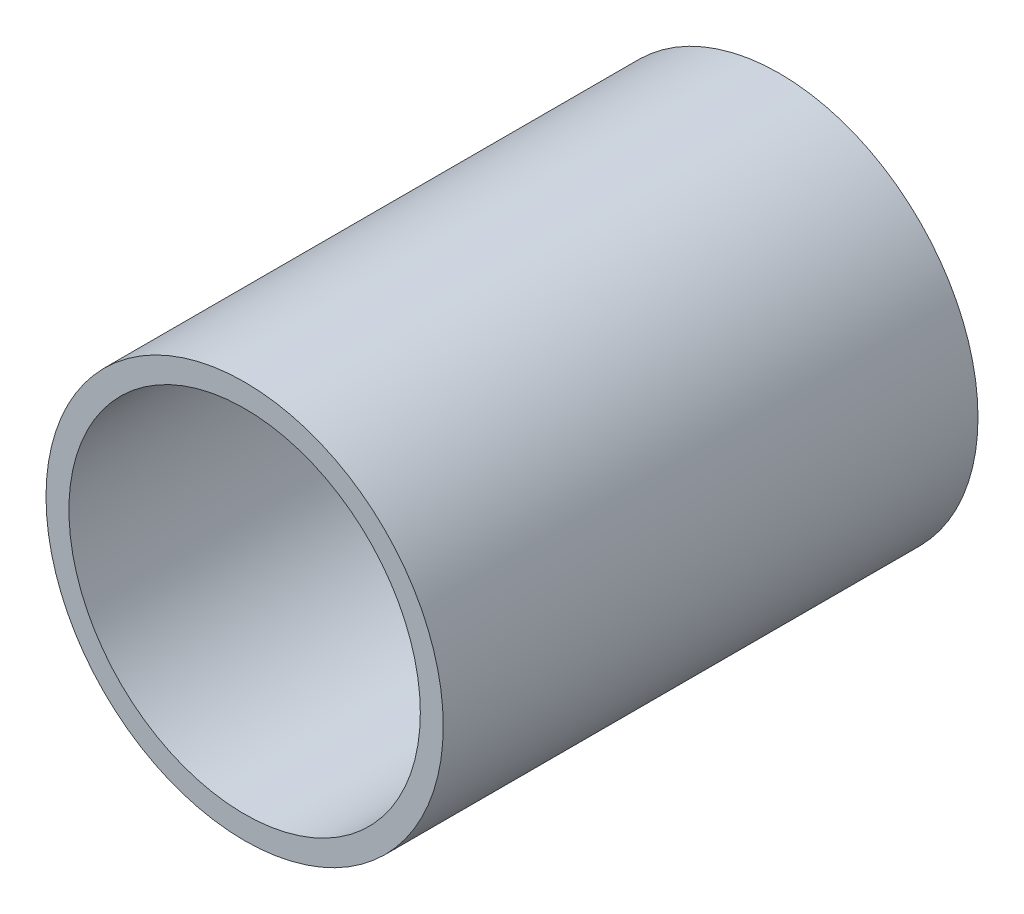
SolidWorks part; units mm, degrees
ref_plane "Front Plane" through (0, 0, 0) normal (1, 0, 0) x (0, 1, 0)
ref_plane "Top Plane" through (0, 0, 0) normal (0, 0, 1) x (0, 1, 0)
ref_plane "Right Plane" through (0, 0, 0) normal (0, 1, 0) x (-1, 0, 0)
sketch "Sketch1" plane through (0, 0, 0) normal (0, 0, 1) x (0, 1, 0)
  circle A0 centre (0, 0) radius 26
  circle A1 centre (0, 0) radius 23
  dimension "D1" = 52
  dimension "D2" = 46
extrude "Boss-Extrude1" add sketch "Sketch1" along normal mid plane 70
